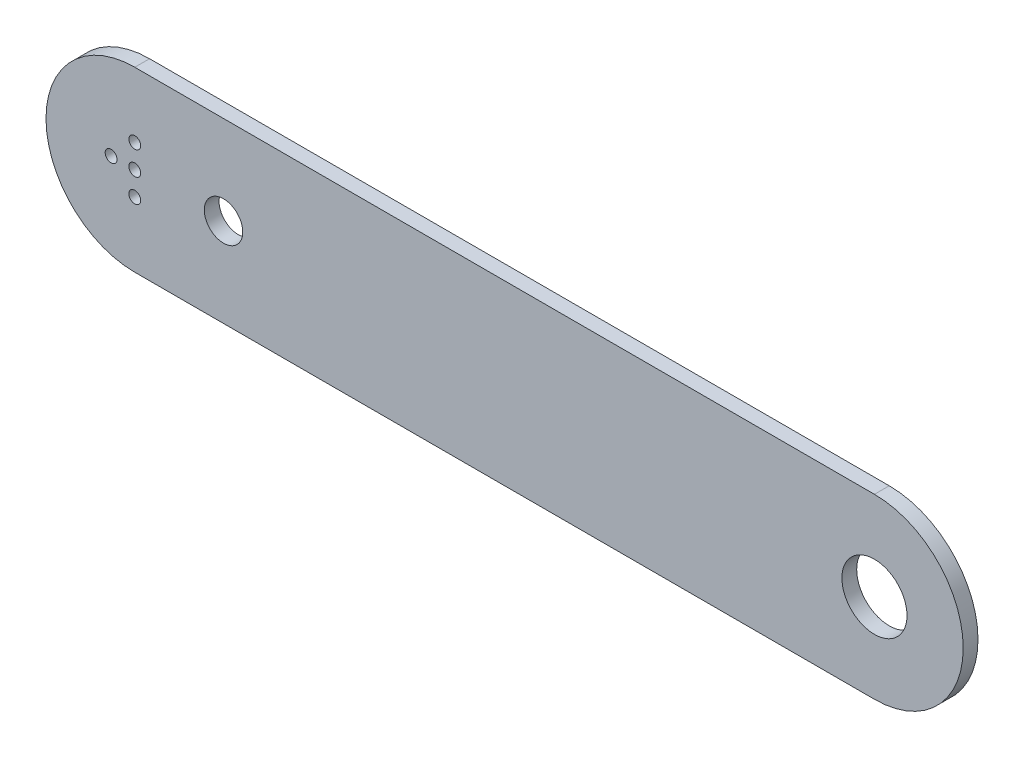
SolidWorks part; units mm, degrees
ref_plane "Alzado" through (0, 0, 0) normal (0, 0, 1) x (1, 0, 0)
ref_plane "Planta" through (0, 0, 0) normal (0, 1, 0) x (1, 0, 0)
ref_plane "Vista lateral" through (0, 0, 0) normal (1, 0, 0) x (0, 0, -1)
sketch "Croquis1" plane through (0, 0, 0) normal (0, 0, 1) x (1, 0, 0)
  line L0 (400, 60) -> (370, 60) construction
  line L1 (120, 0) -> (370, 0)
  line L3 (120, 60) -> (370, 60)
  arc A0 (370, 60) -> (370, 0) centre (370, 30) cw
  arc A3 (120, 60) -> (120, 0) centre (120, 30) ccw
  point P10 (0, 0)
  point P13 (0, 60)
  dimension "D4" = 30
  dimension "D1" = 30
  dimension "D2" = 250
  dimension "D3" = 30
extrude "Saliente-Extruir1" add sketch "Croquis1" along normal blind 5
sketch "Croquis2" plane through (0, 0, 5) normal (0, 0, 1) x (1, 0, 0)
  line L0 (370, 60) -> (370, 0) construction
  line L1 (120, 60) -> (120, 0) construction
  line L3 (43.4976, 30) -> (150, 30) construction
  line L4 (370, 60) -> (120, 60) construction
  circle A0 centre (370, 30) radius 11
  circle A2 centre (150, 30) radius 6.5
  arc A4 (120, 60) -> (120, 0) centre (120, 30) ccw construction
  circle A5 centre (120, 30) radius 2
  circle A7 centre (120, 22) radius 2
  circle A8 centre (120, 38) radius 2
  circle A9 centre (112, 30) radius 2
  dimension "D1" = 22
  dimension "D3" = 4
  dimension "D5" = 13
  dimension "D8" = 4
  dimension "D2" = 220
  dimension "D4" = 8
  dimension "D6" = 8
  dimension "D7" = 8
extrude "Cortar-Extruir4" cut sketch "Croquis2" against normal blind 220
sketch "Croquis6" plane through (0, 0, 5) normal (0, 0, 1) x (1, 0, 0)
  circle A0 centre (150, 30) radius 20
  circle A1 centre (150, 12.518) radius 2
  circle A2 centre (166.3929, 30) radius 2
  circle A3 centre (150, 47.1727) radius 2
  circle A4 centre (133, 30) radius 2
  dimension "D1" = 40
  dimension "D2" = 4
  dimension "D3" = 4
  dimension "D4" = 4
  dimension "D5" = 4
  dimension "D6" = 17
